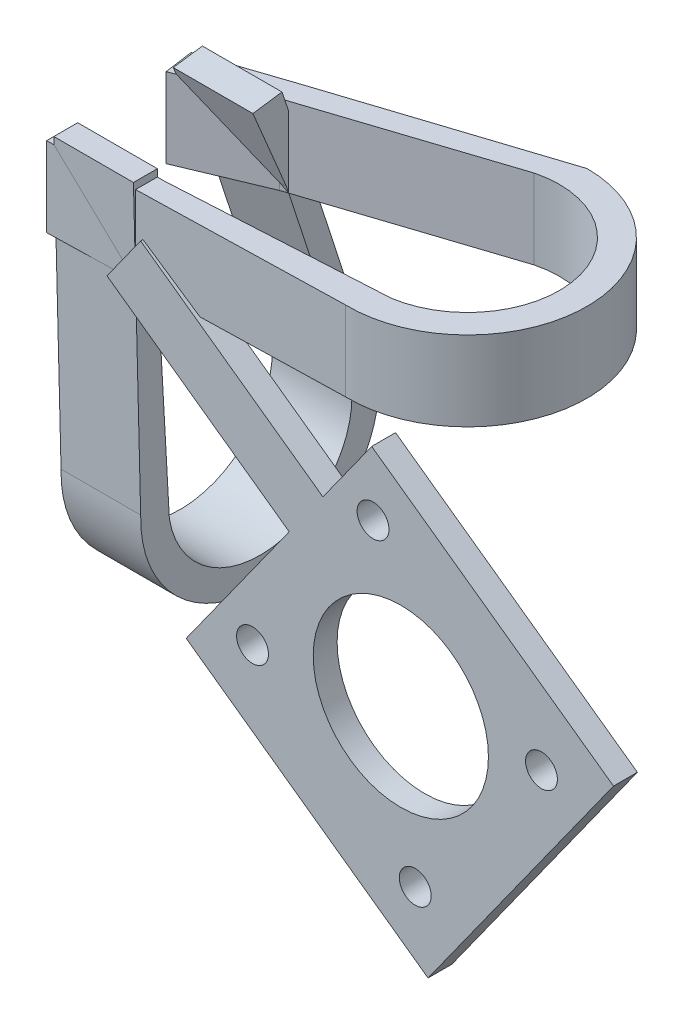
SolidWorks part; units mm, degrees
ref_plane "Front Plane" through (0, 0, 0) normal (0, 0, 1) x (1, 0, 0)
ref_plane "Top Plane" through (0, 0, 0) normal (0, 1, 0) x (1, 0, 0)
ref_plane "Right Plane" through (0, 0, 0) normal (1, 0, 0) x (0, 0, -1)
sketch "Sketch1" plane through (0, 0, 0) normal (0, 1, 0) x (1, 0, 0)
  line L0 (0, 15) -> (-26.9002, 6.2787)
  line L1 (-26.9002, 6.2787) -> (-37.4744, 2.7504)
  line L2 (-36.9587, -0.904) -> (-26.9002, 3.3174)
  line L3 (-0.3257, -14.9965) -> (-36.9587, -15.904)
  line L4 (-36.9587, -15.904) -> (-36.9587, -12.904)
  line L5 (-32.5869, -12.904) -> (-25.1455, -12.904)
  line L6 (-26.9002, 3.3174) -> (-2.8211, 11.1932)
  line L7 (-25.1455, -12.904) -> (1.8518, -11.3937)
  line L8 (-32.5869, -12.904) -> (-36.9587, -12.904)
  line L9 (-37.4744, 2.7504) -> (-36.9587, -0.904)
  arc A0 (-0.3257, -14.9965) -> (0, 15) centre (0, 0) ccw
  arc A1 (1.8518, -11.3937) -> (-2.8211, 11.1932) centre (0, 0) ccw
  dimension "D1" = 30
  dimension "D2" = 12
extrude "Boss-Extrude1" add sketch "Sketch1" along normal blind 10
pattern_circular "CirPattern1" count 2 every 90 about axis through (-31.0521, 5, 0) along (0, 0, 1) of "Boss-Extrude1"
sketch "Sketch3" plane through (-4.5801, 0, -13.7263) normal (-0.3165, 0, -0.9486) x (-0.9486, 0, 0.3165)
sketch "Sketch4" plane through (0, 0, 12.904) normal (0, 0, -1) x (-1, 0, 0)
  line L0 (25.1455, 5) -> (29.376, -0.9066)
  line L1 (25.1455, 5) -> (2.2597, -11.3915)
  line L2 (29.376, -0.9066) -> (6.4902, -17.2981)
  line L4 (25.1455, 10) -> (25.1455, 0) construction
  line L5 (26.0521, -0.9066) -> (36.0521, -0.9066) construction
  line L6 (19.4272, -35.3607) -> (6.4902, -17.2981)
  line L7 (19.4272, -35.3607) -> (-10.9451, -57.1142)
  line L8 (-3.8642, -2.8413) -> (-34.2365, -24.5948)
  line L9 (-10.9451, -57.1142) -> (-34.2365, -24.5948)
  line L10 (2.2597, -11.3915) -> (-3.8642, -2.8413)
  line L11 (-5.5946, -22.359) -> (-13.3396, -11.5454) construction
  line L12 (11.0993, -31.928) -> (4.5954, -36.5863) construction
  line L13 (11.0993, -31.928) -> (-4.0401, -10.7904) construction
  line L14 (-4.0401, -10.7904) -> (11.0993, -31.928) construction
  line L15 (-5.5946, -22.359) -> (3.5296, -21.3592) construction
  line L16 (-7.5255, -29.2772) -> (-4.0401, -10.7904) construction
  line L17 (-7.5255, -29.2772) -> (11.0993, -31.928)
  line L18 (-7.5255, -29.2772) -> (-9.3364, -48.0023) construction
  line L19 (-7.5255, -29.2772) -> (26.0521, 0) construction
  circle A0 centre (-4.0401, -10.7904) radius 2
  circle A1 centre (11.0993, -31.928) radius 2
  circle A3 centre (-25.1896, -27.3947) radius 2
  circle A4 centre (-9.3364, -48.0023) radius 2
  circle A5 centre (-7.5255, -29.2772) radius 11
  dimension "D2" = 4
  dimension "D3" = 4
  dimension "D5" = 26
  dimension "D6" = 8
  dimension "D7" = 17.5
  dimension "D8" = 26
  dimension "D1" = 40
  dimension "D4" = 26
extrude "Boss-Extrude2" add sketch "Sketch4" against normal blind 3 contours L6 L2 L0 L1 L10 L8 L9 L7 | A3 | A1 | A0 | A5 | A4
